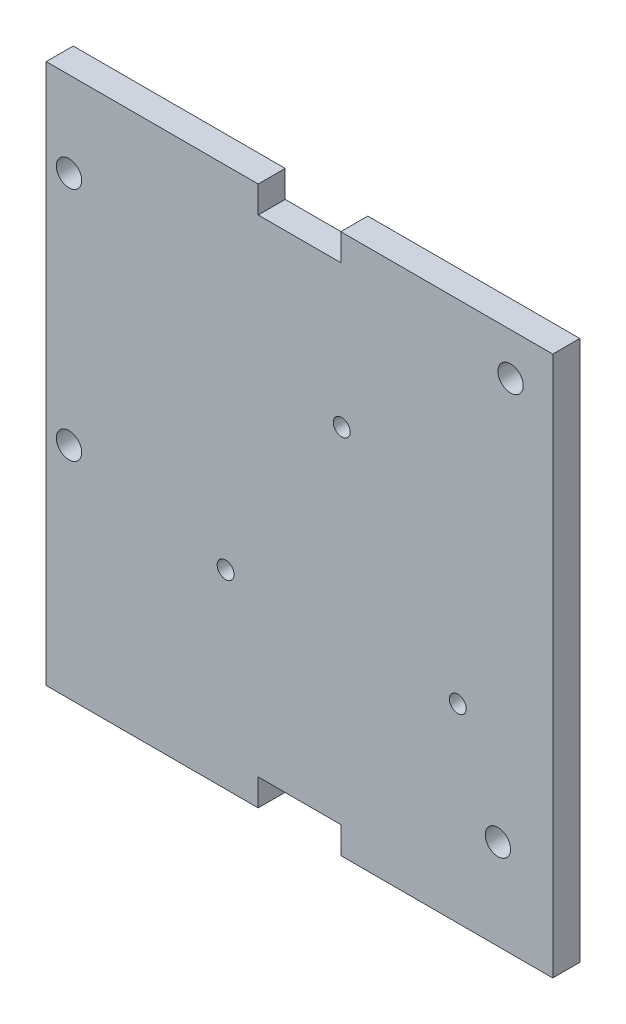
SolidWorks part; units mm, degrees
ref_plane "Front Plane" through (0, 0, 0) normal (0, 0, 1) x (1, 0, 0)
ref_plane "Top Plane" through (0, 0, 0) normal (0, 1, 0) x (1, 0, 0)
ref_plane "Right Plane" through (0, 0, 0) normal (1, 0, 0) x (0, 0, -1)
sketch "Sketch2" plane through (0, 0, 0) normal (0, 0, 1) x (1, 0, 0)
  line L1 (-32.5494, -8.3608) -> (27.4506, -8.3608)
  line L2 (-32.5494, -8.3608) -> (-32.5494, 55.6392)
  line L3 (-32.5494, 55.6392) -> (27.4506, 55.6392)
  line L4 (27.4506, -8.3608) -> (27.4506, 55.6392)
  dimension "D1" = 64
  dimension "D2" = 60
extrude "Top" add sketch "Sketch2" along normal blind 3.2
sketch "Sketch3" plane through (0, 0, 3.2) normal (0, 0, 1) x (1, 0, 0)
  line L0 (22.4506, 50.6392) -> (22.4506, 1.9043) construction
  line L4 (27.4506, 55.6392) -> (-32.5494, 55.6392) construction
  line L6 (27.4506, -8.3608) -> (27.4506, 55.6392) construction
  circle A0 centre (20.9506, 2.3392) radius 1.5
  circle A1 centre (22.4506, 50.6392) radius 1.5
  circle A2 centre (-29.8494, 17.6392) radius 1.5
  circle A3 centre (-29.8494, 45.5392) radius 1.5
  dimension "D1" = 3
  dimension "D2" = 48.3
  dimension "D7" = 5
  dimension "D3" = 27.9
  dimension "D4" = 5.1
  dimension "D5" = 50.8
  dimension "D6" = 5
extrude "Arduino Holes" cut sketch "Sketch3" against normal blind 3.2
sketch "Sketch5" plane through (0, 0, 0) normal (0, 0, -1) x (-1, 0, 0)
  line L0 (-2.4506, 35.6392) -> (-2.4506, 7.8086) construction
  line L3 (-27.4506, 55.6392) -> (32.5494, 55.6392) construction
  line L4 (-27.4506, -8.3608) -> (-27.4506, 55.6392) construction
  circle A0 centre (-2.4506, 35.6392) radius 1
  circle A1 centre (-16.2006, 14.1392) radius 1
  circle A2 centre (11.2994, 14.1392) radius 1
  dimension "D1" = 2
  dimension "D2" = 27.5
  dimension "D3" = 21.5
  dimension "D4" = 20
  dimension "D5" = 25
extrude "Battery Cut" cut sketch "Sketch5" against normal blind 3.2
sketch "Sketch7" plane through (0, 0, 0) normal (0, 0, -1) x (-1, 0, 0)
  line L0 (2.5494, -8.3608) -> (2.5494, 55.6392) construction
  line L1 (32.5494, -8.3608) -> (-27.4506, -8.3608) construction
  line L2 (-27.4506, 55.6392) -> (32.5494, 55.6392) construction
  line L4 (7.4394, 55.6392) -> (-2.3406, 55.6392)
  line L5 (7.4394, 55.6392) -> (7.4394, 52.4592)
  line L6 (7.4394, 52.4592) -> (-2.3406, 52.4592)
  line L7 (-2.3406, 55.6392) -> (-2.3406, 52.4592)
  line L8 (-2.3406, -8.3608) -> (7.4394, -8.3608)
  line L9 (-2.3406, -8.3608) -> (-2.3406, -5.1808)
  line L10 (-2.3406, -5.1808) -> (7.4394, -5.1808)
  line L11 (7.4394, -8.3608) -> (7.4394, -5.1808)
  dimension "D1" = 3.18
  dimension "D2" = 9.78
  dimension "D3" = 3.18
  dimension "D4" = 9.78
extrude "Friction Fit" cut sketch "Sketch7" against normal blind 10
sketch "Sketch4" [suppressed] plane through (0, 0, 0) normal (0, 0, 1) x (1, 0, 0)
  line L0 (0, 13.2972) -> (0, -11.8071) construction
  line L1 (30, -15) -> (-30, -15)
  line L2 (30, -15) -> (30, 15)
  line L3 (30, 15) -> (-30, 15)
  line L4 (-30, -15) -> (-30, 15)
  line L5 (17.7111, 0) -> (-18.0699, 0) construction
  dimension "D1" = 60
  dimension "D2" = 30
extrude "Side" [suppressed] add sketch "Sketch4" along normal blind 3.2
sketch "Sketch8" [suppressed] plane through (0, 15, 0) normal (0, 1, 0) x (1, 0, 0)
  line L0 (30, 0) -> (-30, 0) construction
  line L1 (5.11, 0) -> (-5.11, 0)
  line L2 (5.11, 0) -> (5.11, -3.2)
  line L3 (5.11, -3.2) -> (-5.11, -3.2)
  line L4 (-5.11, 0) -> (-5.11, -3.2)
  line L5 (30, -3.2) -> (-30, -3.2) construction
  line L6 (0, 0) -> (0, -3.2) construction
  dimension "D1" = 10.22
extrude "Friction Extrude" [suppressed] add sketch "Sketch8" along normal blind 3.18
mirror "Mirror" [suppressed] about plane through (0, 0, 0) normal (0, 1, 0)
equation "\"Kerf\"= .22"
